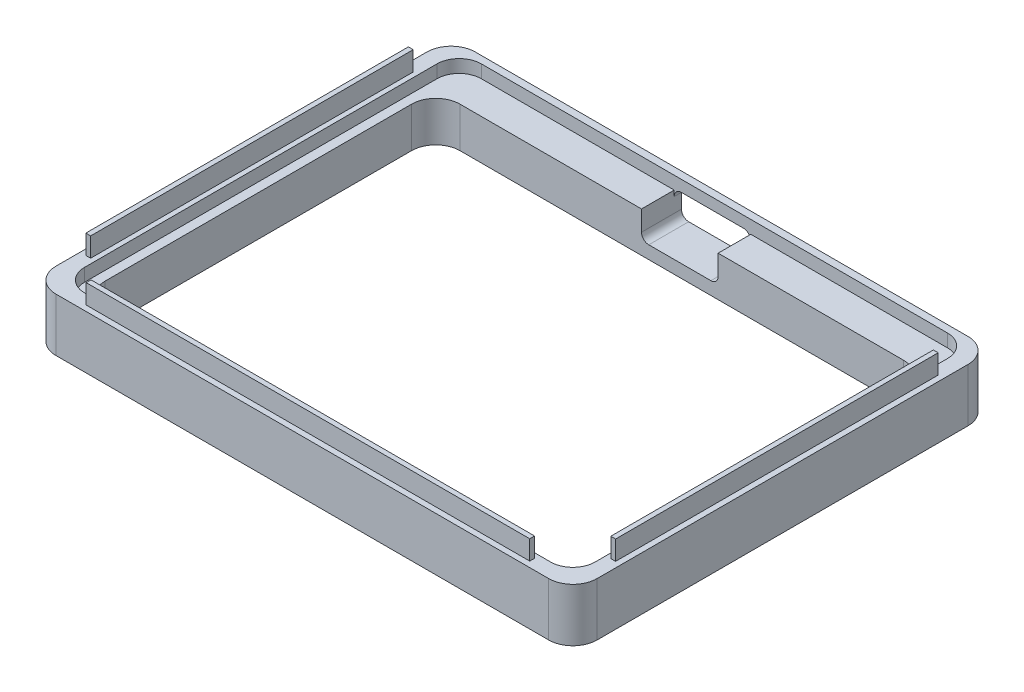
SolidWorks part; units mm, degrees
ref_plane "Front Plane" through (0, 0, 0) normal (0, 0, 1) x (1, 0, 0)
ref_plane "Top Plane" through (0, 0, 0) normal (0, 1, 0) x (1, 0, 0)
ref_plane "Right Plane" through (0, 0, 0) normal (1, 0, 0) x (0, 0, -1)
sketch "Sketch1" plane through (0, 0, 0) normal (0, 1, 0) x (1, 0, 0)
  line L1 (3, 0) -> (64.1, 0)
  line L2 (0, 3) -> (0, 49)
  line L3 (3, 52) -> (64.1, 52)
  line L4 (67.1, 3) -> (67.1, 49)
  arc A0 (3, 0) -> (0, 3) centre (3, 3) cw
  arc A1 (64.1, 0) -> (67.1, 3) centre (64.1, 3) ccw
  arc A2 (64.1, 52) -> (67.1, 49) centre (64.1, 49) cw
  arc A3 (0, 49) -> (3, 52) centre (3, 49) cw
  point P7 (0, 0)
  point P10 (67.1, 0)
  point P13 (67.1, 52)
  dimension "D3" = 3
  dimension "D1" = 67.1
  dimension "D2" = 52
extrude "Boss-Extrude1" add sketch "Sketch1" along normal blind 6.6
sketch "Sketch2" plane through (0, 6.6, 0) normal (0, 1, 0) x (1, 0, 0)
  line L2 (6.05, 3.05) -> (61.05, 3.05)
  line L3 (3.05, 6.05) -> (3.05, 44.05)
  line L4 (6.05, 47.05) -> (61.05, 47.05)
  line L5 (64.05, 6.05) -> (64.05, 44.05)
  line L6 (0, 49) -> (0, 3) construction
  line L7 (3, 0) -> (64.1, 0) construction
  arc A0 (6.05, 3.05) -> (3.05, 6.05) centre (6.05, 6.05) cw
  arc A1 (61.05, 3.05) -> (64.05, 6.05) centre (61.05, 6.05) ccw
  arc A2 (61.05, 47.05) -> (64.05, 44.05) centre (61.05, 44.05) cw
  arc A3 (3.05, 44.05) -> (6.05, 47.05) centre (6.05, 44.05) cw
  point P10 (3.05, 3.05)
  point P13 (64.05, 3.05)
  point P18 (3.05, 47.05)
  dimension "D5" = 3
  dimension "D1" = 61
  dimension "D2" = 44
  dimension "D3" = 3.05
  dimension "D4" = 3.05
extrude "Cut-Extrude1" cut sketch "Sketch2" against normal blind 6.6
sketch "Sketch3" plane through (0, 6.6, 0) normal (0, 1, 0) x (1, 0, 0)
  line L0 (67.1, 3) -> (67.1, 49) construction
  line L1 (4.65, 51.1) -> (62.45, 51.1)
  line L2 (1.9, 48.35) -> (1.9, 4.65)
  line L3 (4.65, 1.9) -> (62.45, 1.9)
  line L4 (65.2, 48.35) -> (65.2, 4.65)
  line L5 (3, 0) -> (64.1, 0) construction
  arc A0 (1.9, 4.65) -> (4.65, 1.9) centre (4.65, 4.65) ccw
  arc A1 (62.45, 1.9) -> (65.2, 4.65) centre (62.45, 4.65) ccw
  arc A2 (62.45, 51.1) -> (65.2, 48.35) centre (62.45, 48.35) cw
  arc A3 (4.65, 51.1) -> (1.9, 48.35) centre (4.65, 48.35) ccw
  point P10 (1.9, 1.9)
  point P13 (65.2, 1.9)
  point P16 (65.2, 51.1)
  dimension "D5" = 2.75
  dimension "D1" = 49.2
  dimension "D2" = 63.3
  dimension "D3" = 1.9
  dimension "D4" = 1.9
extrude "Cut-Extrude2" cut sketch "Sketch3" against normal blind 1.6
sketch "Sketch4" plane through (0, 0, -52) normal (0, 0, -1) x (-1, 0, 0)
  line L0 (0, 6.6) -> (0, 0) construction
  line L1 (-37.16, 5.2) -> (-29.46, 5.2)
  line L2 (-38.06, 4.3) -> (-38.06, 2.5)
  line L3 (-37.16, 1.6) -> (-29.46, 1.6)
  line L4 (-28.56, 4.3) -> (-28.56, 2.5)
  line L5 (-64.1, 6.6) -> (-3, 6.6) construction
  arc A0 (-37.16, 5.2) -> (-38.06, 4.3) centre (-37.16, 4.3) ccw
  arc A1 (-38.06, 2.5) -> (-37.16, 1.6) centre (-37.16, 2.5) ccw
  arc A2 (-29.46, 1.6) -> (-28.56, 2.5) centre (-29.46, 2.5) ccw
  arc A3 (-29.46, 5.2) -> (-28.56, 4.3) centre (-29.46, 4.3) cw
  point P10 (-38.06, 1.6)
  point P13 (-28.56, 1.6)
  point P16 (-28.56, 5.2)
  dimension "D4" = 0.9
  dimension "D1" = 1.4
  dimension "D2" = 3.6
  dimension "D3" = 9.5
  dimension "D5" = 28.56
extrude "Cut-Extrude3" cut sketch "Sketch4" against normal blind 11.6
sketch "Sketch5" plane through (0, 5, 0) normal (0, 1, 0) x (1, 0, 0)
  line L0 (28.8943, 51.1) -> (37.7257, 51.1) construction
  line L5 (33.31, 51.1) -> (33.31, 47.05) construction
  line L6 (28.8943, 51.1) -> (4.65, 51.1) construction
  line L7 (28.56, 51.1) -> (38.06, 51.1)
  line L8 (28.56, 51.1) -> (28.56, 47.05)
  line L9 (28.56, 47.05) -> (38.06, 47.05)
  line L10 (38.06, 51.1) -> (38.06, 47.05)
  line L11 (37.7257, 47.05) -> (61.05, 47.05) construction
  line L12 (37.16, 47.05) -> (29.46, 47.05) construction
  line L13 (33.31, 51.1) -> (33.31, 47.05) construction
  dimension "D1" = 9.5
extrude "Cut-Extrude4" cut sketch "Sketch5" against normal blind 2
sketch "Sketch6" plane through (0, 0, 0) normal (0, -1, 0) x (1, 0, 0)
  line L0 (0, -26) -> (67.1, -26) construction
  line L1 (65.6, -6) -> (66.35, -6)
  line L2 (0.75, -6) -> (1.5, -6)
  line L3 (0.75, -6) -> (0.75, -46)
  line L4 (0.75, -46) -> (1.5, -46)
  line L5 (1.5, -6) -> (1.5, -46)
  line L6 (65.6, -6) -> (65.6, -46)
  line L7 (65.6, -46) -> (66.35, -46)
  line L8 (66.35, -6) -> (66.35, -46)
  line L9 (6.05, -0.75) -> (61.05, -0.75)
  line L10 (6.05, -0.75) -> (6.05, -1.5)
  line L11 (6.05, -1.5) -> (61.05, -1.5)
  line L12 (61.05, -0.75) -> (61.05, -1.5)
  line L13 (0, -49) -> (0, -3) construction
  line L14 (67.1, -3) -> (67.1, -49) construction
  line L15 (33.55, -52) -> (33.55, 0) construction
  line L16 (64.1, -52) -> (3, -52) construction
  line L17 (3, 0) -> (64.1, 0) construction
  line L18 (64.05, -6.05) -> (64.05, -44.05) construction
  line L31 (6.05, -3.05) -> (61.05, -3.05) construction
  point P11 (66.35, -26)
  point P16 (33.55, -1.5)
  point P21 (1.5, -26)
  dimension "D1" = 0.75
  dimension "D2" = 40
  dimension "D3" = 55
  dimension "D4" = 0.75
  dimension "D5" = 0.75
  dimension "D6" = 0.75
  dimension "D7" = 0.75
extrude "Cut-Extrude5" cut sketch "Sketch6" against normal blind 2.6
sketch "Sketch7" plane through (0, 6.6, 0) normal (0, 1, 0) x (1, 0, 0)
  line L0 (65.2, 4.65) -> (65.2, 48.35) construction
  line L1 (0.7, 46) -> (1.3, 46)
  line L2 (0.7, 46) -> (0.7, 6)
  line L3 (0.7, 6) -> (1.3, 6)
  line L4 (1.3, 46) -> (1.3, 6)
  line L5 (6.05, 1.3) -> (61.05, 1.3)
  line L6 (6.05, 1.3) -> (6.05, 0.7)
  line L7 (6.05, 0.7) -> (61.05, 0.7)
  line L8 (61.05, 1.3) -> (61.05, 0.7)
  line L9 (65.8, 46) -> (66.4, 46)
  line L10 (65.8, 46) -> (65.8, 6)
  line L11 (65.8, 6) -> (66.4, 6)
  line L12 (66.4, 46) -> (66.4, 6)
  line L13 (4.65, 1.9) -> (62.45, 1.9) construction
  line L14 (1.9, 48.35) -> (1.9, 4.65) construction
  line L15 (0, 26) -> (67.1, 26) construction
  line L16 (0, 49) -> (0, 3) construction
  line L17 (67.1, 3) -> (67.1, 49) construction
  line L18 (33.55, 52) -> (33.55, 0) construction
  line L19 (64.1, 52) -> (3, 52) construction
  line L20 (3, 0) -> (64.1, 0) construction
  point P24 (65.8, 26)
  point P25 (1.3, 26)
  point P32 (33.55, 1.3)
  dimension "D1" = 0.6
  dimension "D2" = 0.6
  dimension "D3" = 0.6
  dimension "D4" = 0.6
  dimension "D5" = 40
  dimension "D6" = 55
extrude "Boss-Extrude2" add sketch "Sketch7" along normal blind 2.4
